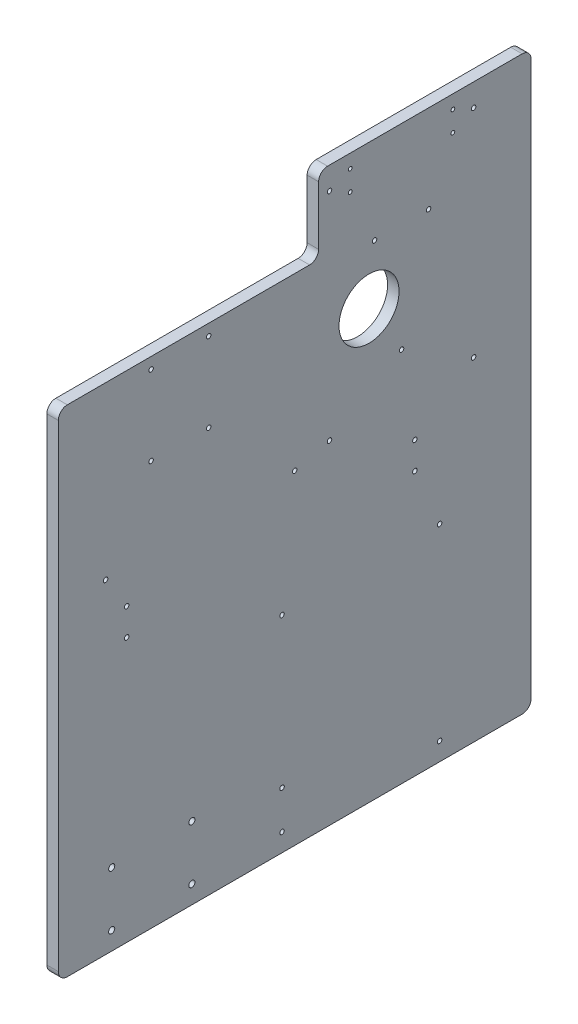
SolidWorks part; units mm, degrees
material "Low Carbon Steel"
ref_plane "Front Plane" through (0, 0, 0) normal (0, 0, 1) x (1, 0, 0)
ref_plane "Top Plane" through (0, 0, 0) normal (0, 1, 0) x (1, 0, 0)
ref_plane "Right Plane" through (0, 0, 0) normal (1, 0, 0) x (0, 0, -1)
sketch "Sketch1" plane through (0, 0, 0) normal (1, 0, 0) x (0, 0, -1)
  line L0 (-262.5, -317.5) -> (262.5, 317.5) construction
  line L1 (26.5, 317.5) -> (262.5, 317.5)
  line L2 (-262.5, 232.5) -> (-262.5, -317.5)
  line L3 (-262.5, -317.5) -> (262.5, -317.5)
  line L4 (262.5, 317.5) -> (262.5, -317.5)
  line L5 (-262.5, 232.5) -> (26.5, 232.5)
  line L6 (26.5, 232.5) -> (26.5, 317.5)
  circle A0 centre (82.5, 157.5) radius 33.3375
  dimension "D7" = 66.675
  dimension "D6" = 160
  dimension "D1" = 525
  dimension "D2" = 635
  dimension "D3" = 236
  dimension "D4" = 85
  dimension "D5" = 180
extrude "Boss-Extrude1" add sketch "Sketch1" along normal blind 12.7
fillet "Fillet1" radius 10 6 edges at (6.35, -317.5, -262.5) (6.35, -317.5, 262.5) (6.35, 317.5, -262.5) (6.35, 317.5, -26.5) (6.35, 232.5, -26.5) (6.35, 232.5, 262.5)
hole_wizard "M5 Tapped Hole1" positions "Sketch3" profile "Sketch2" tap size "M5" standard "Peddi DIN"
sketch "Sketch3" plane through (12.7, 0, 0) normal (1, 0, 0) x (0, 0, -1)
  line L0 (175.625, 302.5) -> (175.625, 280) construction
  line L1 (175.625, 280) -> (61.625, 280) construction
  line L2 (61.625, 280) -> (61.625, 302.5) construction
  line L4 (252.5, 317.5) -> (36.5, 317.5) construction
  line L5 (262.5, -307.5) -> (262.5, 307.5) construction
  point P0 (175.625, 302.5)
  point P2 (175.625, 280)
  point P4 (61.625, 280)
  point P6 (61.625, 302.5)
  dimension "D1" = 22.5
  dimension "D2" = 114
  dimension "D3" = 37.5
  dimension "D4" = 86.875
sketch "Sketch2" plane through (12.7, 302.5, -175.625) normal (0, 1, 0) x (0, 0, -1)
  line L0 (0, 0) -> (0, 15.2618)
  line L1 (0, 15.2618) -> (2.1, 14)
  line L2 (2.1, 14) -> (2.1, 0)
  line L5 (2.1, 0) -> (0, 0)
  line L10 (0, 15.2618) -> (-2.1, 14) construction
  line L11 (0, -6.35) -> (0, 107.95) construction
  dimension "Tap Drill Dia." = 4.2
  dimension "Tap Drill Depth" = 14
  dimension "Drill Angle" = 118
cosmetic thread "Hole Thread1"
cosmetic thread "Hole Thread2"
cosmetic thread "Hole Thread3"
cosmetic thread "Hole Thread4"
hole_wizard "M6 Tapped Hole1" positions "Sketch5" profile "Sketch4" tap size "M6" standard "Peddi DIN" end condition through all
sketch "Sketch5" plane through (12.7, 0, 0) normal (1, 0, 0) x (0, 0, -1)
  line L1 (-186.5876, 5.8122) -> (133.4124, 5.8122) construction
  line L2 (-186.5876, 5.8122) -> (-186.5876, -24.1878) construction
  line L3 (-186.5876, -24.1878) -> (133.4124, -24.1878) construction
  line L4 (133.4124, 5.8122) -> (133.4124, -24.1878) construction
  circle A0 centre (175.625, 280) radius 2.1 construction
  point P0 (-186.5876, 5.8122)
  point P2 (-186.5876, -24.1878)
  point P4 (133.4124, 5.8122)
  point P6 (133.4124, -24.1878)
  dimension "D1" = 30
  dimension "D2" = 320
  dimension "D3" = 274.1878
  dimension "D4" = 42.2126
cosmetic thread "Hole Thread5"
cosmetic thread "Hole Thread6"
cosmetic thread "Hole Thread7"
cosmetic thread "Hole Thread8"
sketch "Sketch4" plane through (12.7, 5.8122, 186.5876) normal (0, 1, 0) x (0, 0, -1)
  line L0 (0, 0) -> (0, 12.7)
  line L1 (0, 12.7) -> (2.5, 12.7)
  line L2 (2.5, 12.7) -> (2.5, 0)
  line L5 (2.5, 0) -> (0, 0)
  line L11 (0, -6.35) -> (0, 107.95) construction
  dimension "Thru Tap Drill Dia." = 5
  dimension "Thru Tap Drill Depth" = 12.7
hole_wizard "M6 Tapped Hole2" positions "Sketch7" profile "Sketch6" tap size "M6" standard "Peddi DIN" end condition through all
sketch "Sketch7" plane through (12.7, 0, 0) normal (1, 0, 0) x (0, 0, -1)
  line L0 (-210.0133, 42.8878) -> (-0.0133, 42.8878) construction
  circle A0 centre (133.4124, 5.8122) radius 2.5 construction
  circle A1 centre (-186.5876, 5.8122) radius 2.5 construction
  point P0 (-210.0133, 42.8878)
  point P3 (-0.0133, 42.8878)
  dimension "D2" = 133.4257
  dimension "D1" = 210
  dimension "D3" = 37.0757
sketch "Sketch6" plane through (12.7, 42.8878, 210.0133) normal (0, 1, 0) x (0, 0, -1)
  line L0 (0, 0) -> (0, 12.7)
  line L1 (0, 12.7) -> (2.5, 12.7)
  line L2 (2.5, 12.7) -> (2.5, 0)
  line L5 (2.5, 0) -> (0, 0)
  line L11 (0, -6.35) -> (0, 107.95) construction
  dimension "Thru Tap Drill Dia." = 5
  dimension "Thru Tap Drill Depth" = 12.7
cosmetic thread "Hole Thread9"
cosmetic thread "Hole Thread10"
hole_wizard "M6 Tapped Hole3" positions "Sketch9" profile "Sketch8" tap size "M6" standard "Peddi DIN" end condition through all
sketch "Sketch9" plane through (12.7, 0, 0) normal (1, 0, 0) x (0, 0, -1)
  line L0 (148.625, 160) -> (88.625, 160) construction
  line L2 (148.625, 220) -> (148.625, 160) construction
  line L4 (118.625, 160) -> (118.625, 100) construction
  line L6 (61.625, 280) -> (175.625, 280) construction
  line L8 (118.625, 160) -> (118.625, 280) construction
  point P0 (88.625, 220)
  point P2 (148.625, 220)
  point P4 (118.625, 100)
  dimension "D1" = 60
  dimension "D2" = 60
  dimension "D3" = 60
  dimension "D4" = 120
sketch "Sketch8" plane through (12.7, 220, -88.625) normal (0, 1, 0) x (0, 0, -1)
  line L0 (0, 0) -> (0, 12.7)
  line L1 (0, 12.7) -> (2.5, 12.7)
  line L2 (2.5, 12.7) -> (2.5, 0)
  line L5 (2.5, 0) -> (0, 0)
  line L11 (0, -6.35) -> (0, 107.95) construction
  dimension "Thru Tap Drill Dia." = 5
  dimension "Thru Tap Drill Depth" = 12.7
cosmetic thread "Hole Thread11"
cosmetic thread "Hole Thread12"
cosmetic thread "Hole Thread18"
hole_wizard "M6 Tapped Hole4" positions "Sketch11" profile "Sketch10" tap size "M6" standard "Peddi DIN" end condition through all
sketch "Sketch11" plane through (12.7, 0, 0) normal (1, 0, 0) x (0, 0, -1)
  line L0 (38.625, 52.5) -> (198.625, 52.5) construction
  line L1 (198.625, 52.5) -> (198.625, 292.5) construction
  line L2 (198.625, 292.5) -> (38.625, 292.5) construction
  line L4 (252.5, 317.5) -> (36.5, 317.5) construction
  line L5 (61.625, 280) -> (175.625, 280) construction
  line L7 (118.625, 280) -> (118.625, 292.5) construction
  point P0 (198.625, 292.5)
  point P2 (38.625, 292.5)
  point P4 (38.625, 52.5)
  point P6 (198.625, 52.5)
  dimension "D1" = 25
  dimension "D2" = 160
  dimension "D3" = 240
sketch "Sketch10" plane through (12.7, 292.5, -198.625) normal (0, 1, 0) x (0, 0, -1)
  line L0 (0, 0) -> (0, 12.7)
  line L1 (0, 12.7) -> (2.5, 12.7)
  line L2 (2.5, 12.7) -> (2.5, 0)
  line L5 (2.5, 0) -> (0, 0)
  line L11 (0, -6.35) -> (0, 107.95) construction
  dimension "Thru Tap Drill Dia." = 5
  dimension "Thru Tap Drill Depth" = 12.7
cosmetic thread "Hole Thread14"
cosmetic thread "Hole Thread15"
cosmetic thread "Hole Thread16"
cosmetic thread "Hole Thread17"
hole_wizard "M6 Tapped Hole5" positions "Sketch12" profile "Sketch13" tap size "M6" standard "Peddi DIN" end condition through all
sketch "Sketch12" plane through (12.7, 0, 0) normal (1, 0, 0) x (0, 0, -1)
  line L18 (252.5, 317.5) -> (36.5, 317.5) construction
  line L19 (262.5, -307.5) -> (262.5, 307.5) construction
  line L20 (-14.1, -254.9) -> (-14.1, -297.4) construction
  line L21 (-14.1, -297.4) -> (160.9, -297.4) construction
  point P0 (-14.1, -254.9)
  point P2 (-14.1, -88.9)
  point P4 (160.9, -297.4)
  point P6 (160.9, -88.9)
  point P63 (-14.1, -297.4)
  dimension "D1" = 406.4
  dimension "D2" = 208.5
  dimension "D3" = 166
  dimension "D4" = 175
  dimension "D5" = 101.6
sketch "Sketch13" plane through (12.7, -254.9, 14.1) normal (0, 1, 0) x (0, 0, -1)
  line L0 (0, 0) -> (0, 12.7)
  line L1 (0, 12.7) -> (2.5, 12.7)
  line L2 (2.5, 12.7) -> (2.5, 0)
  line L5 (2.5, 0) -> (0, 0)
  line L11 (0, -6.35) -> (0, 107.95) construction
  dimension "Thru Tap Drill Dia." = 5
  dimension "Thru Tap Drill Depth" = 12.7
cosmetic thread "Hole Thread26"
cosmetic thread "Hole Thread27"
cosmetic thread "Hole Thread28"
cosmetic thread "Hole Thread29"
cosmetic thread "Hole Thread39"
hole_wizard "M8 Tapped Hole1" positions "Sketch16" profile "Sketch17" tap size "M8" standard "Peddi DIN" end condition through all
sketch "Sketch16" plane through (12.7, 0, 0) normal (1, 0, 0) x (0, 0, -1)
  line L1 (-203.2135, -237.075) -> (-114.1865, -237.075) construction
  line L2 (-203.2135, -237.075) -> (-203.2135, -297.4) construction
  line L3 (-203.2135, -297.4) -> (-114.1865, -297.4) construction
  line L4 (-114.1865, -237.075) -> (-114.1865, -297.4) construction
  line L5 (-158.7, -237.075) -> (-158.7, -297.4) construction
  line L8 (-203.2135, -267.2375) -> (-114.1865, -267.2375) construction
  line L10 (262.5, -307.5) -> (262.5, 307.5) construction
  line L12 (160.9, -297.4) -> (-114.1865, -297.4) construction
  point P0 (-203.2135, -237.075)
  point P2 (-114.1865, -237.075)
  point P4 (-114.1865, -297.4)
  point P6 (-203.2135, -297.4)
  dimension "D1" = 89.027
  dimension "D2" = 60.325
  dimension "D3" = 421.2
sketch "Sketch17" plane through (12.7, -237.075, 203.2135) normal (0, 1, 0) x (0, 0, -1)
  line L0 (0, 0) -> (0, 12.7)
  line L1 (0, 12.7) -> (3.4, 12.7)
  line L2 (3.4, 12.7) -> (3.4, 0)
  line L5 (3.4, 0) -> (0, 0)
  line L11 (0, -6.35) -> (0, 107.95) construction
  dimension "Thru Tap Drill Dia." = 6.8
  dimension "Thru Tap Drill Depth" = 12.7
cosmetic thread "Hole Thread31"
cosmetic thread "Hole Thread32"
cosmetic thread "Hole Thread33"
cosmetic thread "Hole Thread34"
hole_wizard "M6 Tapped Hole6" positions "Sketch18" profile "Sketch19" tap size "M6" standard "Peddi DIN" end condition through all
sketch "Sketch18" plane through (12.7, 0, 0) normal (1, 0, 0) x (0, 0, -1)
  line L1 (-159.5, 220) -> (-95.5, 220) construction
  line L2 (-159.5, 220) -> (-159.5, 132) construction
  line L3 (-159.5, 132) -> (-95.5, 132) construction
  line L4 (-95.5, 220) -> (-95.5, 132) construction
  line L7 (-127.5, 220) -> (-127.5, 132) construction
  line L9 (262.5, -307.5) -> (262.5, 307.5) construction
  line L10 (88.625, 220) -> (-95.5, 220) construction
  point P0 (-159.5, 220)
  point P2 (-95.5, 220)
  point P4 (-95.5, 132)
  point P6 (-159.5, 132)
  dimension "D1" = 64
  dimension "D2" = 88
  dimension "D4" = 390
sketch "Sketch19" plane through (12.7, 220, 159.5) normal (0, 1, 0) x (0, 0, -1)
  line L0 (0, 0) -> (0, 12.7)
  line L1 (0, 12.7) -> (2.5, 12.7)
  line L2 (2.5, 12.7) -> (2.5, 0)
  line L5 (2.5, 0) -> (0, 0)
  line L11 (0, -6.35) -> (0, 107.95) construction
  dimension "Thru Tap Drill Dia." = 5
  dimension "Thru Tap Drill Depth" = 12.7
cosmetic thread "Hole Thread35"
cosmetic thread "Hole Thread36"
cosmetic thread "Hole Thread37"
cosmetic thread "Hole Thread38"
other "Freeze***"
